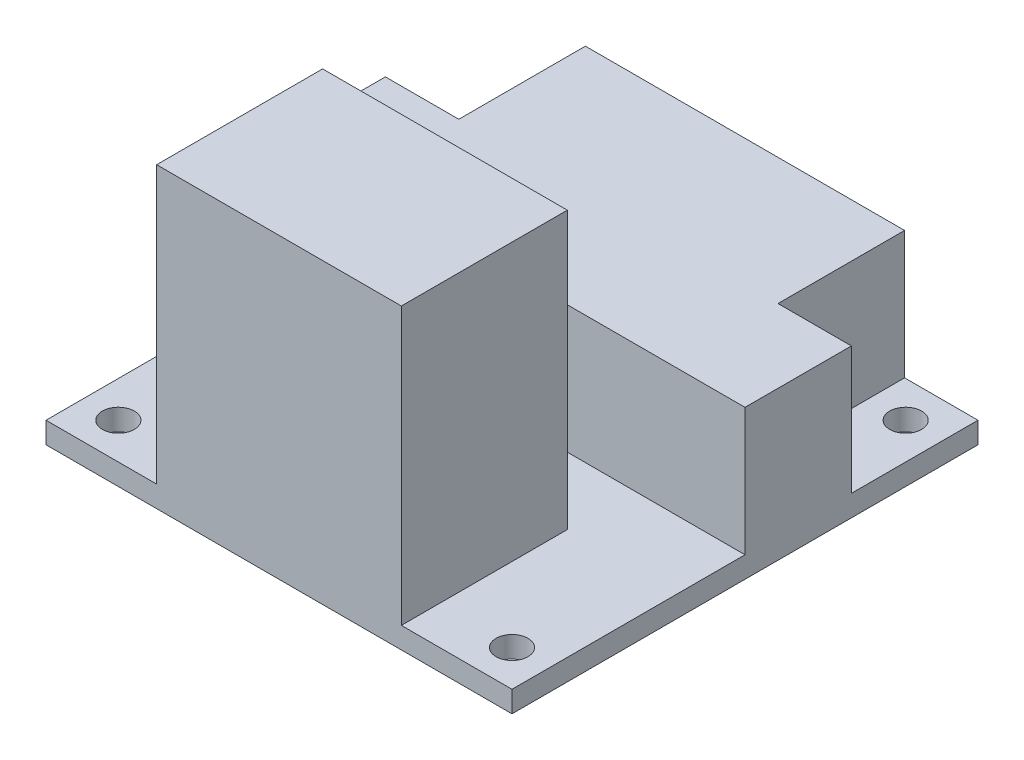
SolidWorks part; units mm, degrees
ref_plane "Plano frontal" through (0, 0, 0) normal (0, 0, 1) x (1, 0, 0)
ref_plane "Plano superior" through (0, 0, 0) normal (0, 1, 0) x (1, 0, 0)
ref_plane "Plano direito" through (0, 0, 0) normal (1, 0, 0) x (0, 0, -1)
sketch "Esboço1" plane through (0, 0, 0) normal (0, 1, 0) x (1, 0, 0)
  line L0 (18.5, 18.5) -> (-18.5, 18.5) construction
  line L1 (-21.9, -21.9) -> (21.9, -21.9)
  line L2 (-21.9, -21.9) -> (-21.9, 21.9)
  line L3 (-21.9, 21.9) -> (21.9, 21.9)
  line L4 (21.9, -21.9) -> (21.9, 21.9)
  line L5 (-21.9, -21.9) -> (21.9, 21.9) construction
  line L6 (-21.9, 21.9) -> (21.9, -21.9) construction
  line L7 (18.5, 18.5) -> (18.5, -18.5) construction
  line L8 (18.5, -18.5) -> (-18.5, -18.5) construction
  line L9 (-18.5, -18.5) -> (-18.5, 18.5) construction
  circle A0 centre (18.5, 18.5) radius 1.5
  circle A1 centre (-18.5, 18.5) radius 1.5
  circle A2 centre (18.5, -18.5) radius 1.5
  circle A3 centre (-18.5, -18.5) radius 1.5
  point P0 (0, 0)
  dimension "D3" = 3
  dimension "D4" = 3
  dimension "D5" = 3
  dimension "D7" = 3
  dimension "D1" = 43.8
  dimension "D2" = 43.8
  dimension "D6" = 3.4
extrude "Ressalto-extrusão1" add sketch "Esboço1" along normal blind 2
sketch "Esboço2" plane through (0, 2, 0) normal (0, 1, 0) x (1, 0, 0)
  line L0 (0, 0) -> (0, -21.9) construction
  line L1 (-21.9, -21.9) -> (21.9, -21.9) construction
  line L3 (-11.5, -21.9) -> (11.5, -21.9)
  line L4 (-11.5, -21.9) -> (-11.5, -6.3)
  line L5 (-11.5, -6.3) -> (11.5, -6.3)
  line L6 (11.5, -21.9) -> (11.5, -6.3)
  line L7 (-11.5, -21.9) -> (11.5, -6.3) construction
  line L8 (-11.5, -6.3) -> (11.5, -21.9) construction
  point P5 (0, -14.1)
  point P10 (0, -12.3878)
  dimension "D1" = 23
  dimension "D2" = 15.6
extrude "Ressalto-extrusão2" add sketch "Esboço2" along normal blind 26
sketch "Esboço3" plane through (0, 2, 0) normal (0, 1, 0) x (1, 0, 0)
  line L0 (0, 0) -> (0, 21.9) construction
  line L1 (21.9, 21.9) -> (-21.9, 21.9) construction
  line L2 (21.9, -21.9) -> (21.9, 21.9) construction
  line L3 (-15, 0) -> (15, 0)
  line L4 (-15, 0) -> (-15, 21.9)
  line L5 (-15, 21.9) -> (15, 21.9)
  line L6 (15, 0) -> (15, 21.9)
  line L7 (-15, 0) -> (15, 21.9) construction
  line L8 (-15, 21.9) -> (15, 0) construction
  line L9 (-21.9, 10) -> (21.9, 10)
  line L10 (-21.9, 10) -> (-21.9, 0)
  line L11 (-21.9, 0) -> (21.9, 0)
  line L12 (21.9, 10) -> (21.9, 0)
  line L13 (-21.9, 10) -> (21.9, 0) construction
  line L14 (-21.9, 0) -> (21.9, 10) construction
  point P5 (0, 10.95)
  point P10 (0, 5)
  line M15 (21.9, -21.9) -> (21.9, 21.9)
  line M16 (21.9, 21.9) -> (-21.9, 21.9)
  line M17 (-21.9, 21.9) -> (-21.9, -21.9)
  dimension "D1" = 30
  dimension "D2" = 10
extrude "Ressalto-extrusão3" add sketch "Esboço3" along normal blind 12 contours L11 L4 L9 M17 | L6 L11 L9 M15 | L4 L9 L6 M16 | L9 L4 L3 L6
